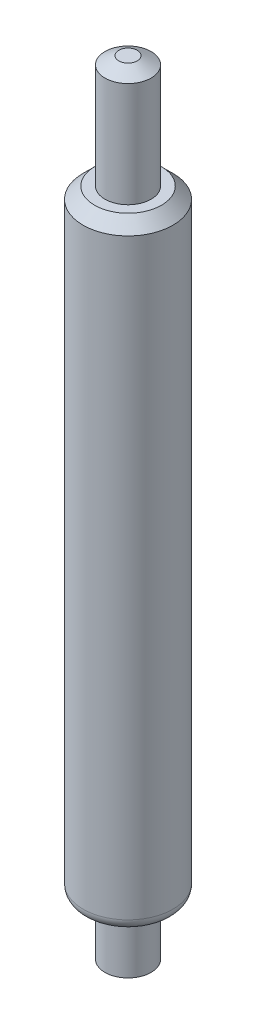
SolidWorks part; units mm, degrees
ref_plane "Front Plane" through (0, 0, 0) normal (0, 0, 1) x (1, 0, 0)
ref_plane "Top Plane" through (0, 0, 0) normal (0, 1, 0) x (1, 0, 0)
ref_plane "Right Plane" through (0, 0, 0) normal (1, 0, 0) x (0, 0, -1)
sketch "Sketch1" plane through (0, 0, 0) normal (0, 0, 1) x (1, 0, 0)
  line L0 (0, -1.0575) -> (0, 1.5785) construction
  line L1 (0, 1.715) -> (0.1, 1.715)
  line L2 (0.1, 1.715) -> (0.1, 1.225)
  line L3 (0.1, 1.225) -> (0.195, 1.225)
  line L4 (0.195, 1.225) -> (0.195, -1.445)
  line L5 (0.195, -1.445) -> (0.1, -1.445)
  line L6 (0.1, -1.445) -> (0.1, -1.715)
  line L7 (0.1, -1.715) -> (0, -1.715)
  line L8 (0, -1.715) -> (0, 1.715)
  point P5 (0.195, -1.2233)
  dimension "D1" = 0.1
  dimension "D2" = 0.195
  dimension "D3" = 0.49
  dimension "D4" = 2.67
  dimension "D5" = 0.27
  dimension "D6" = 1.715
revolve "Revolve1" add sketch "Sketch1" angle 360 about L0
chamfer "Chamfer1" distance 0.06 angle 30 1 edges at (0, 1.715, -0.1)
chamfer "Chamfer2" distance 0.06 angle 30 1 edges at (0, -1.715, -0.1)
chamfer "Chamfer3" distance 0.05 angle 45 1 edges at (0, 1.225, -0.195)
fillet "Fillet1" radius 0.05 1 edges at (0, -1.445, -0.195)
